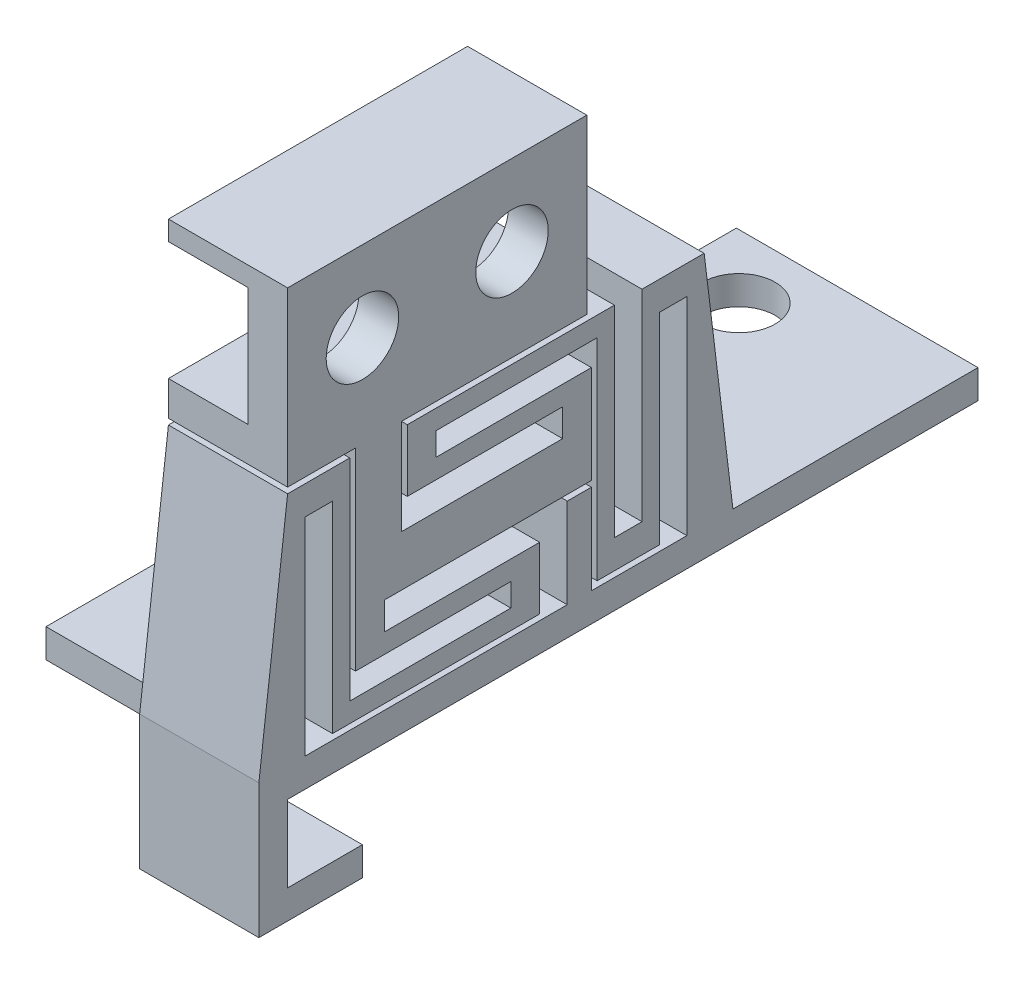
SolidWorks part; units mm, degrees
ref_plane "Front Plane" through (0, 0, 0) normal (0, 0, 1) x (1, 0, 0)
ref_plane "Top Plane" through (0, 0, 0) normal (0, 1, 0) x (1, 0, 0)
ref_plane "Right Plane" through (0, 0, 0) normal (1, 0, 0) x (0, 0, -1)
sketch "Sketch1" plane through (0, 0, 0) normal (1, 0, 0) x (0, 0, -1)
  line L0 (0, 0) -> (13, 0)
  line L1 (13, 0) -> (13, -7.5)
  line L2 (0, 0) -> (0, -7.5)
  line L3 (0, -7.5) -> (2.95, -7.5)
  line L4 (2.95, -7.5) -> (2.95, -15.9)
  line L5 (2.95, -15.9) -> (9.7, -15.9)
  line L6 (9.7, -15.9) -> (9.7, -16.9)
  line L7 (9.7, -16.9) -> (2.7, -16.9)
  line L8 (2.7, -16.9) -> (2.7, -7.75)
  line L9 (2.7, -7.75) -> (0, -7.75)
  line L10 (0, -7.75) -> (-1.25, -18)
  line L11 (13, -7.5) -> (4.95, -7.5)
  line L12 (4.95, -7.5) -> (4.95, -11.65)
  line L13 (4.95, -11.65) -> (11.95, -11.65)
  line L14 (11.95, -11.65) -> (11.95, -10.45)
  line L15 (11.95, -10.45) -> (5.2, -10.45)
  line L16 (5.2, -10.45) -> (5.2, -7.75)
  line L17 (5.2, -7.75) -> (14.2, -7.75)
  line L18 (13.2, -9.6) -> (13.2, -13.85)
  line L19 (13.2, -13.85) -> (4.2, -13.85)
  line L20 (4.2, -13.85) -> (4.2, -15.05)
  line L21 (4.2, -15.05) -> (10.95, -15.05)
  line L22 (10.95, -15.05) -> (10.95, -17.75)
  line L23 (10.95, -17.75) -> (1.95, -17.75)
  line L24 (1.95, -17.75) -> (1.95, -9)
  line L25 (1.95, -9) -> (0.75, -9)
  line L26 (0.75, -9) -> (0.75, -18)
  line L27 (0.75, -18) -> (17.35, -18)
  line L28 (13.2, -9.6) -> (6.45, -9.6)
  line L29 (6.45, -9.6) -> (6.45, -8.6)
  line L30 (6.45, -8.6) -> (13.45, -8.6)
  line L31 (13.45, -8.6) -> (13.45, -17.75)
  line L32 (14.2, -7.75) -> (14.2, -16.5)
  line L33 (14.2, -16.5) -> (15.4, -16.5)
  line L34 (15.4, -16.5) -> (15.4, -7.75)
  line L35 (15.4, -7.75) -> (18.1, -7.75)
  line L36 (13.45, -17.75) -> (16.15, -17.75)
  line L37 (16.15, -17.75) -> (16.15, -9)
  line L38 (16.15, -9) -> (17.35, -9)
  line L39 (17.35, -9) -> (17.35, -18)
  line L45 (0, -19.25) -> (19.35, -19.25)
  line L47 (19.35, -19.25) -> (19.35, -18)
  line L49 (18.1, -7.75) -> (19.35, -18)
  line L51 (-1.25, -18) -> (-1.25, -23.83)
  line L52 (-1.25, -23.83) -> (3.25, -23.83)
  line L53 (3.25, -23.83) -> (3.25, -22.58)
  line L54 (3.25, -22.58) -> (0, -22.58)
  line L55 (0, -22.58) -> (0, -19.25)
  point P49 (6.45, -17.75)
  point P53 (11.95, -11.05)
  dimension "D2" = 2.7
  dimension "D3" = 0.75
  dimension "D4" = 1.2
  dimension "D5" = 7
  dimension "D6" = 1.25
  dimension "D7" = 7
  dimension "D8" = 2.7
  dimension "D9" = 0.75
  dimension "D10" = 1.2
  dimension "D11" = 2.7
  dimension "D12" = 7.5
  dimension "D13" = 0.25
  dimension "D14" = 1.25
  dimension "D15" = 10
  dimension "D16" = 0.25
  dimension "D17" = 1.25
  dimension "D20" = 13
  dimension "D21" = 0.25
  dimension "D22" = 2.7
  dimension "D23" = 0.85
  dimension "D24" = 1
  dimension "D25" = 1.2
  dimension "D26" = 1.25
  dimension "D27" = 0.25
  dimension "D29" = 0.85
  dimension "D28" = 1.25
  dimension "D30" = 1.25
  dimension "D31" = 1.2
  dimension "D18" = 1.25
  dimension "D19" = 4.5
  dimension "D32" = 1.25
  dimension "D33" = 3.33
  dimension "D34" = 1.25
  dimension "D35" = 2
  dimension "D36" = 0.25
  dimension "D37" = 1.25
extrude "Boss-Extrude1" add sketch "Sketch1" along normal blind 5.18
sketch "Sketch2" plane through (0, 0, 0) normal (0, 0, 1) x (1, 0, 0)
  line L0 (5.18, 0) -> (5.18, -7.5) construction
  line L1 (5.18, -0.85) -> (1.73, -0.85)
  line L2 (5.18, -0.85) -> (5.18, -6)
  line L3 (5.18, -6) -> (1.73, -6)
  line L4 (1.73, -0.85) -> (1.73, -6)
  line L6 (5.18, -7.5) -> (0, -7.5) construction
  line L7 (5.18, 0) -> (0, 0) construction
  dimension "D1" = 3.45
  dimension "D2" = 1.5
  dimension "D3" = 0.85
extrude "Cut-Extrude1" cut sketch "Sketch2" against normal up to next
sketch "Sketch3" plane through (0, -19.25, 0) normal (0, -1, 0) x (1, 0, 0)
  line L0 (0, 1.25) -> (0, -3.25) construction
  line L1 (0, -30) -> (10.5, -30)
  line L2 (0, -30) -> (0, 0)
  line L3 (0, 0) -> (10.5, 0)
  line L4 (10.5, -30) -> (10.5, 0)
  line L6 (5.18, 0) -> (5.18, -19.35) construction
  line L7 (5.18, 1.25) -> (0, 1.25) construction
  circle A0 centre (7.62, -15.23) radius 1.575
  circle A1 centre (7.62, -27.23) radius 1.575
  dimension "D3" = 3.15
  dimension "D1" = 10.5
  dimension "D2" = 16.48
  dimension "D4" = 12
  dimension "D5" = 30
  dimension "D6" = 2.44
extrude "Boss-Extrude2" add sketch "Sketch3" against normal blind 1.25
sketch "Sketch7" plane through (0, 0, 0) normal (-1, 0, 0) x (0, 0, 1)
  line L0 (-13, 0) -> (0, 0) construction
  line L1 (0, 0) -> (0, -7.5) construction
  circle A0 centre (-3.25, -3.5) radius 1.575
  circle A1 centre (-9.75, -3.5) radius 1.575
  dimension "D1" = 3.15
  dimension "D2" = 3.5
  dimension "D3" = 3.25
  dimension "D4" = 6.5
extrude "Cut-Extrude3" cut sketch "Sketch7" against normal up to next
sketch "Sketch9" plane through (0, 0, 0) normal (-1, 0, 0) x (0, 0, 1)
  line L0 (-0.75, -18) -> (-17.35, -18) construction
  line L1 (-13.2, -18) -> (-12.15, -18)
  line L2 (-13.2, -18) -> (-13.2, -14.1)
  line L3 (-13.2, -14.1) -> (-12.15, -14.1)
  line L4 (-12.15, -18) -> (-12.15, -14.1)
  line L5 (-13.2, -13.85) -> (-4.2, -13.85) construction
  line L6 (-13.45, -17.75) -> (-13.45, -8.6) construction
  line L7 (-10.95, -15.05) -> (-10.95, -17.75) construction
  dimension "D1" = 0.25
  dimension "D2" = 0.25
  dimension "D3" = 1.2
extrude "Boss-Extrude3" add sketch "Sketch9" against normal blind 5.18
mirror "Mirror3" about plane through (0, 0, 0) normal (1, 0, 0) of bodies 109 105
delete or keep bodies "Body-Delete/Keep 1" type delete bodies bodies 109
equation "\"VerticalFlexureWidth\"= 0.75"
equation "\"VerticalFlexureGap\"= 1.2"
equation "\"VerticalDoubleFlexureWidth\"= 2 * \"VerticalFlexureWidth\" + \"VerticalFlexureGap\""
equation "\"D2@Sketch1\"=\"VerticalDoubleFlexureWidth\""
equation "\"D3@Sketch1\"=\"VerticalFlexureWidth\""
equation "\"D4@Sketch1\"=\"VerticalFlexureGap\""
equation "\"HorizontalFlexureLength\"= 7"
equation "\"FlexureJointWidth\"= 1.25"
equation "\"D5@Sketch1\"=\"HorizontalFlexureLength\""
equation "\"D6@Sketch1\"=\"FlexureJointWidth\""
equation "\"D7@Sketch1\"=\"HorizontalFlexureLength\""
equation "\"D8@Sketch1\"=\"VerticalDoubleFlexureWidth\""
equation "\"D9@Sketch1\"=\"VerticalFlexureWidth\""
equation "\"D10@Sketch1\"=\"VerticalFlexureGap\""
equation "\"D11@Sketch1\"=\"VerticalDoubleFlexureWidth\""
equation "\"HeadHeight\"= 7.5"
equation "\"VerticalFlexureLength\"= 10"
equation "\"MinGap\"= 0.25"
equation "\"D12@Sketch1\"=\"HeadHeight\""
equation "\"D13@Sketch1\"=\"MinGap\""
equation "\"D14@Sketch1\"=\"FlexureJointWidth\""
equation "\"D15@Sketch1\"=\"VerticalFlexureLength\""
equation "\"D16@Sketch1\"=\"MinGap\""
equation "\"D17@Sketch1\"=\"FlexureJointWidth\""
equation "\"BaseplateHeight+Tolerance\"= 3.33"
equation "\"HeadWidth\"= 13"
equation "\"D20@Sketch1\"=\"HeadWidth\""
equation "\"D21@Sketch1\"=\"MinGap\""
equation "\"D22@Sketch1\"=\"HorizontalDoubleFlexureWidth\""
equation "\"D23@Sketch1\"=\"HorizontalFlexureWidth\""
equation "\"D24@Sketch1\"=\"HorizontalFlexureGap\""
equation "\"D25@Sketch1\"=\"VerticalFlexureGap\""
equation "\"D26@Sketch1\"=\"FlexureJointWidth\""
equation "\"D27@Sketch1\"=\"MinGap\""
equation "\"D29@Sketch1\"=\"HorizontalFlexureWidth\""
equation "\"D28@Sketch1\"=\"FlexureJointWidth\""
equation "\"D30@Sketch1\"=\"FlexureJointWidth\""
equation "\"D31@Sketch1\"=\"VerticalFlexureGap\""
equation "\"D1@Boss-Extrude1\"=5.18"
equation "\"D32@Sketch1\"=\"FlexureJointWidth\""
equation "\"D18@Sketch1\"=\"FlexureJointWidth\""
equation "\"HorizontalFlexureWidth\"= 0.85"
equation "\"HorizontalFlexureGap\"= 1"
equation "\"HorizontalDoubleFlexureWidth\"= 2 * \"HorizontalFlexureWidth\" + \"HorizontalFlexureGap\""
equation "\"D34@Sketch1\"=\"FlexureJointWidth\""
equation "\"D36@Sketch1\"=\"MinGap\""
equation "\"D37@Sketch1\"=\"FlexureJointWidth\""
equation "\"D1@Boss-Extrude2\"=\"FlexureJointWidth\""
equation "\"D1@Sketch9\"=\"MinGap\""
equation "\"D2@Sketch9\"=\"MinGap\""
equation "\"D3@Sketch9\"=\"VerticalFlexureGap\""
